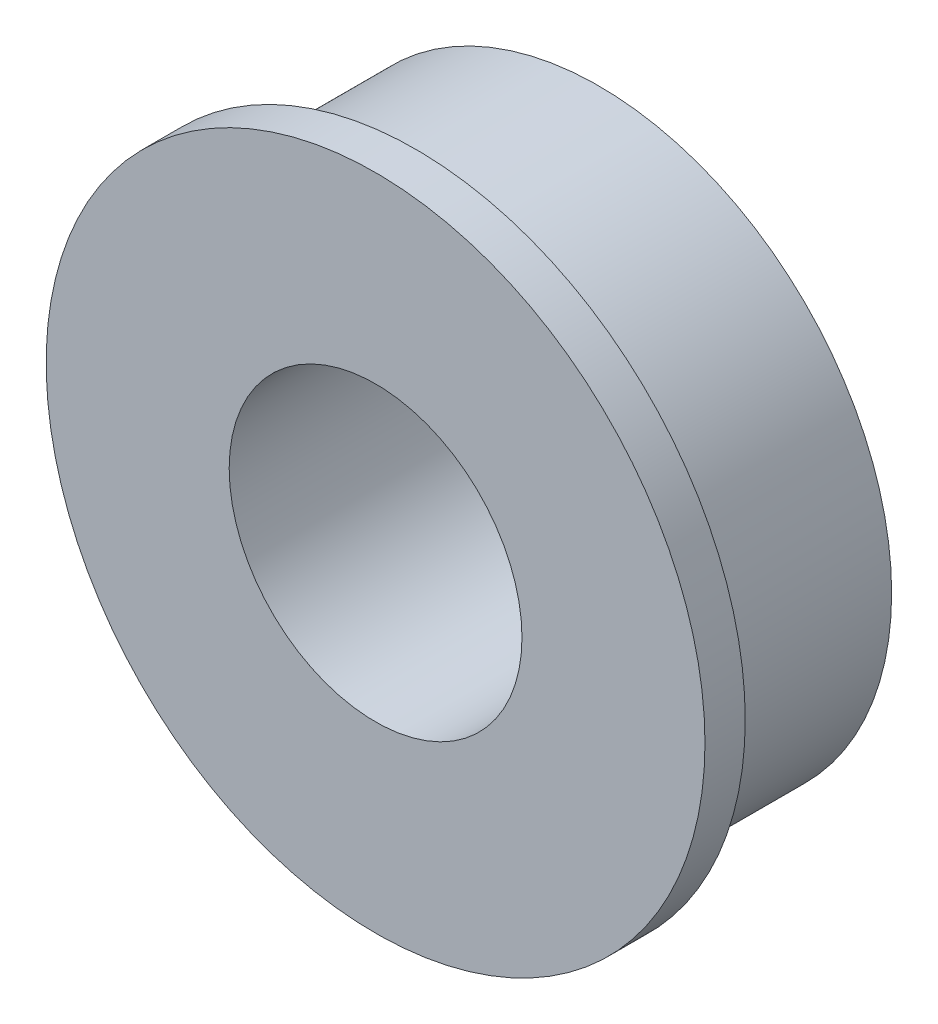
SolidWorks part; units mm, degrees
ref_plane "前视基准面" through (0, 0, 0) normal (0, 0, 1) x (1, 0, 0)
ref_plane "上视基准面" through (0, 0, 0) normal (0, 1, 0) x (1, 0, 0)
ref_plane "右视基准面" through (0, 0, 0) normal (1, 0, 0) x (0, 0, -1)
other "Configuration Table"
sketch "草图1" plane through (0, 0, 0) normal (0, 0, 1) x (1, 0, 0)
  circle A0 centre (0, 0) radius 8
  circle A1 centre (0, 0) radius 4
  dimension "D1" = 16
  dimension "D2" = 8
extrude "凸台-拉伸1" add sketch "草图1" along normal blind 5
sketch "草图2" plane through (0, 0, 5) normal (0, 0, 1) x (1, 0, 0)
  circle A0 centre (0, 0) radius 9
  circle A1 centre (0, 0) radius 4 construction
  circle A2 centre (0, 0) radius 4
  dimension "D1" = 18
extrude "凸台-拉伸2" add sketch "草图2" along normal blind 1.1
